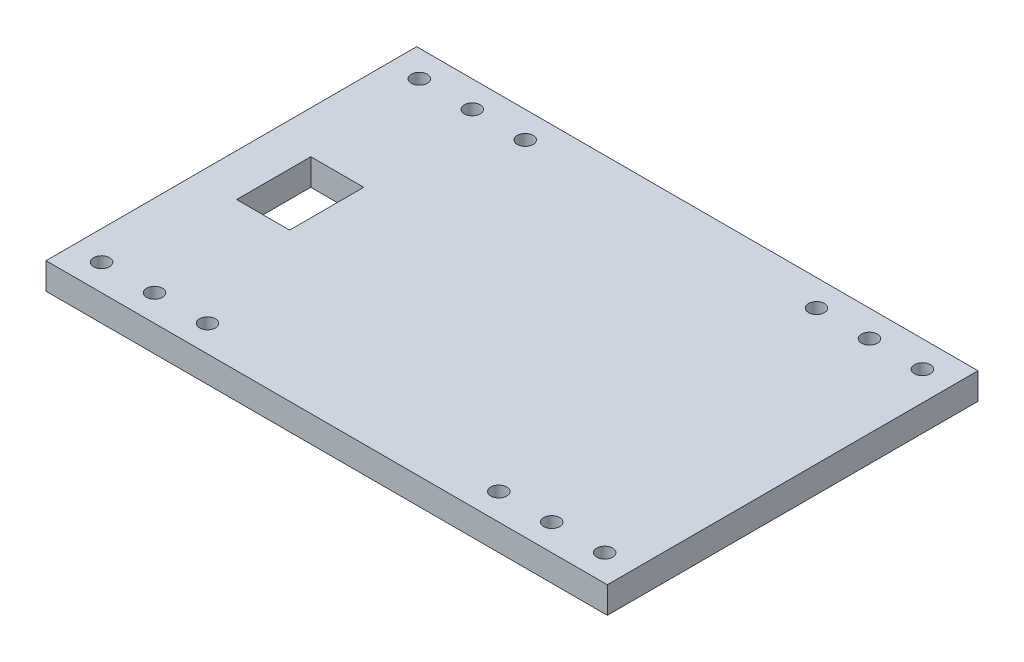
SolidWorks part; units mm, degrees
ref_plane "Front Plane" through (0, 0, 0) normal (0, 0, 1) x (1, 0, 0)
ref_plane "Top Plane" through (0, 0, 0) normal (0, 1, 0) x (1, 0, 0)
ref_plane "Right Plane" through (0, 0, 0) normal (1, 0, 0) x (0, 0, -1)
sketch "Sketch1" plane through (0, 0, 0) normal (0, 1, 0) x (1, 0, 0)
  line L1 (-60, -35) -> (60, -35)
  line L2 (-60, -35) -> (-60, 35)
  line L3 (-60, 35) -> (60, 35)
  line L4 (60, -35) -> (60, 35)
  line L5 (-60, -35) -> (60, 35) construction
  line L6 (-60, 35) -> (60, -35) construction
  point P0 (0, 0)
  dimension "D1" = 70
  dimension "D2" = 120
extrude "Boss-Extrude1" add sketch "Sketch1" along normal blind 5
sketch "Sketch2" plane through (0, 5, 0) normal (0, 1, 0) x (1, 0, 0)
  line L0 (-40, 0) -> (0, 0) construction
  line L7 (-45, 7) -> (-35, 7)
  line L8 (-45, 7) -> (-45, -7)
  line L9 (-45, -7) -> (-35, -7)
  line L10 (-35, 7) -> (-35, -7)
  line L11 (-45, 7) -> (-35, -7) construction
  line L12 (-45, -7) -> (-35, 7) construction
  point P0 (0, 0)
  point P10 (-40, 0)
  dimension "D1" = 40
  dimension "D3" = 10
  dimension "D4" = 14
extrude "Cut-Extrude1" cut sketch "Sketch2" against normal through all both
sketch "Sketch3" plane through (0, 5, 0) normal (0, 1, 0) x (1, 0, 0)
  line L0 (-60, -35) -> (60, -35) construction
  line L1 (60, 35) -> (53, 35)
  line L2 (60, 35) -> (60, -35)
  line L3 (60, -35) -> (53, -35)
  line L4 (53, 35) -> (53, -35)
  line L5 (60, 35) -> (53, -35) construction
  line L6 (60, -35) -> (53, 35) construction
  line L8 (-60, 35) -> (-53, 35)
  line L9 (-60, 35) -> (-60, -35)
  line L10 (-60, -35) -> (-53, -35)
  line L11 (-53, 35) -> (-53, -35)
  line L12 (-60, 35) -> (-53, -35) construction
  line L13 (-60, -35) -> (-53, 35) construction
  point P4 (56.5, 0)
  point P12 (-56.5, 0)
  dimension "D1" = 7
  dimension "D2" = 7
extrude "Cut-Extrude2" cut sketch "Sketch3" against normal through all both
sketch "Sketch4" plane through (0, 5, 0) normal (0, 1, 0) x (1, 0, 0)
  line L0 (-53, -35) -> (53, -35) construction
  line L2 (0, 0) -> (-53, 0) construction
  line L3 (-53, -35) -> (-53, 35) construction
  line L4 (-53, -30) -> (-22, -30) construction
  line L5 (0, 0) -> (0, -35) construction
  circle A0 centre (-37.5, -30) radius 1.5
  circle A1 centre (-27.5, -30) radius 1.5
  circle A2 centre (-47.5, -30) radius 1.5
  circle A3 centre (27.5, -30) radius 1.5
  circle A4 centre (47.5, -30) radius 1.5
  circle A5 centre (37.5, -30) radius 1.5
  circle A6 centre (47.5, 30) radius 1.5
  circle A7 centre (37.5, 30) radius 1.5
  circle A8 centre (27.5, 30) radius 1.5
  circle A9 centre (-27.5, 30) radius 1.5
  circle A10 centre (-37.5, 30) radius 1.5
  circle A11 centre (-47.5, 30) radius 1.5
  dimension "D3" = 3
  dimension "D1" = 31
  dimension "D2" = 5
  dimension "D6" = 10
  dimension "D7" = 10
  dimension "D4" = 2
  dimension "D5" = 2
extrude "Cut-Extrude3" cut sketch "Sketch4" against normal through all both
